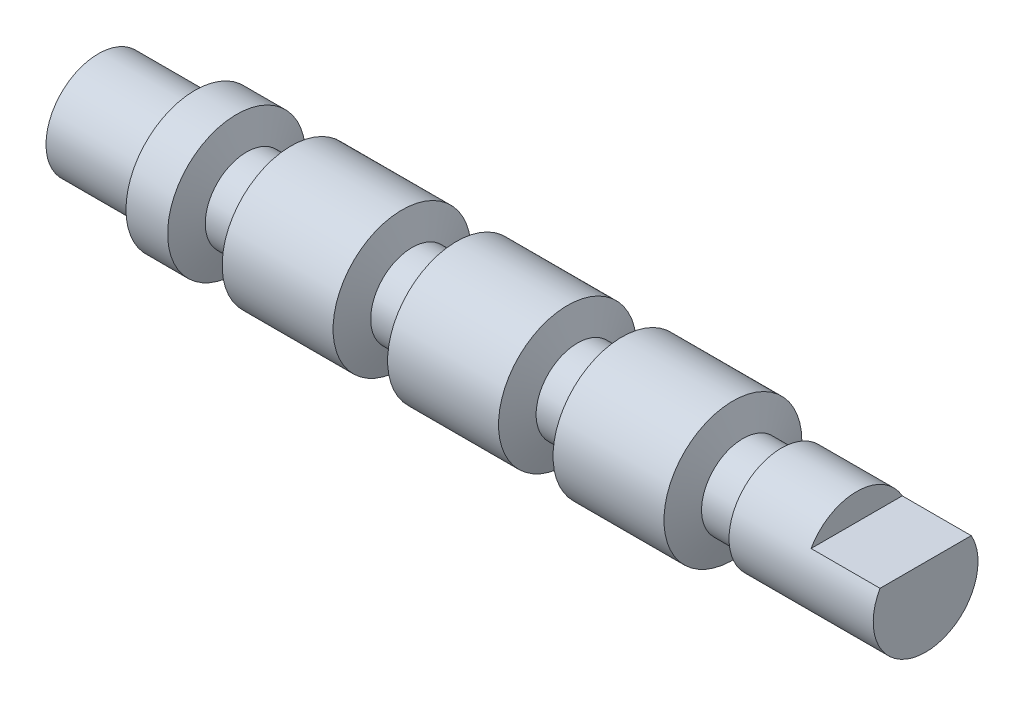
SolidWorks part; units mm, degrees
ref_plane "Front Plane" through (0, 0, 0) normal (0, 0, 1) x (1, 0, 0)
ref_plane "Top Plane" through (0, 0, 0) normal (0, 1, 0) x (1, 0, 0)
ref_plane "Right Plane" through (0, 0, 0) normal (1, 0, 0) x (0, 0, -1)
sketch "Sketch2" plane through (0, 0, 0) normal (0, 1, 0) x (1, 0, 0)
  line L1 (30, -5) -> (-30, -5)
  line L6 (-4.0221, 0) -> (-4.75, -2)
  line L7 (-4.75, -2) -> (-7.25, -2)
  line L8 (-7.25, -2) -> (-7.9779, 0)
  line L9 (-16.0221, 0) -> (-16.75, -2)
  line L10 (-16.75, -2) -> (-19.25, -2)
  line L11 (-19.25, -2) -> (-19.9779, 0)
  line L21 (-4.0221, 0) -> (4.0221, 0)
  line L22 (-16.0221, 0) -> (-7.9779, 0)
  line L25 (-19.9779, 0) -> (-30, 0)
  line L30 (-30, 0) -> (-30, -5)
  line L31 (0, 0) -> (0, -5) construction
  line L42 (30, 0) -> (30, -5)
  line L43 (19.9779, 0) -> (30, 0)
  line L44 (16.0221, 0) -> (7.9779, 0)
  line L45 (19.25, -2) -> (19.9779, 0)
  line L46 (16.75, -2) -> (19.25, -2)
  line L47 (16.0221, 0) -> (16.75, -2)
  line L48 (7.25, -2) -> (7.9779, 0)
  line L49 (4.75, -2) -> (7.25, -2)
  line L50 (4.0221, 0) -> (4.75, -2)
  point P2 (-6, -2)
  point P6 (-18, -2)
  point P25 (0, 0)
  point P26 (0, 0)
  point P27 (0, 0)
  point P28 (-29.9984, 0)
  point P29 (0, 0)
  point P30 (0, 0)
  dimension "D4" = 110
  dimension "D5" = 110
  dimension "D7" = 2.5
  dimension "D9" = 110
  dimension "D10" = 110
  dimension "D11" = 2.5
  dimension "D3" = 3
  dimension "D2" = 5
  dimension "D6" = 6
  dimension "D8" = 18
  dimension "D12" = 30
revolve "Revolve1" add sketch "Sketch2" angle 360 about L1
sketch "Sketch4" plane through (-30, 0, 0) normal (-1, 0, 0) x (0, 0, 1)
  circle A0 centre (5, 0) radius 3.8
  circle A2 centre (5, 0) radius 5
  circle A3 centre (5, 0) radius 5
  dimension "D1" = 7.6
  dimension "D2" = 0
extrude "Cut-Extrude2" cut sketch "Sketch4" against normal blind 7
sketch "Sketch6" plane through (30, 0, 0) normal (1, 0, 0) x (0, 0, -1)
  circle A1 centre (-5, 0) radius 5
  circle A2 centre (-5, 0) radius 5
  circle A3 centre (-5, 0) radius 3.8
  circle A4 centre (-5, 0) radius 3.8
  dimension "D1" = 0
  dimension "D2" = 0
extrude "Cut-Extrude6" cut sketch "Sketch6" against normal blind 12
sketch "Sketch5" plane through (30, 0, 0) normal (1, 0, 0) x (0, 0, -1)
  line L0 (-8.3076, 1.8709) -> (-1.6924, 1.8709)
  line L1 (0, 0) -> (-5, 0) construction
  circle A3 centre (-5, 0) radius 3.8
  arc A4 (-1.6924, 1.8709) -> (-8.3076, 1.8709) centre (-5, 0) ccw
  point P4 (-1.6924, 1.8709)
  point P7 (-1.6924, 1.8709)
  dimension "D2" = 1.8709
  dimension "D3" = 0
extrude "Cut-Extrude5" cut sketch "Sketch5" against normal blind 5
equation "\"Length\"= 60mm"
equation "\"D6@Sketch2\"=\"Length\"/10"
equation "\"D8@Sketch2\"=\"Length\"*3/10"
equation "\"D12@Sketch2\"=\"Length\"/2"
